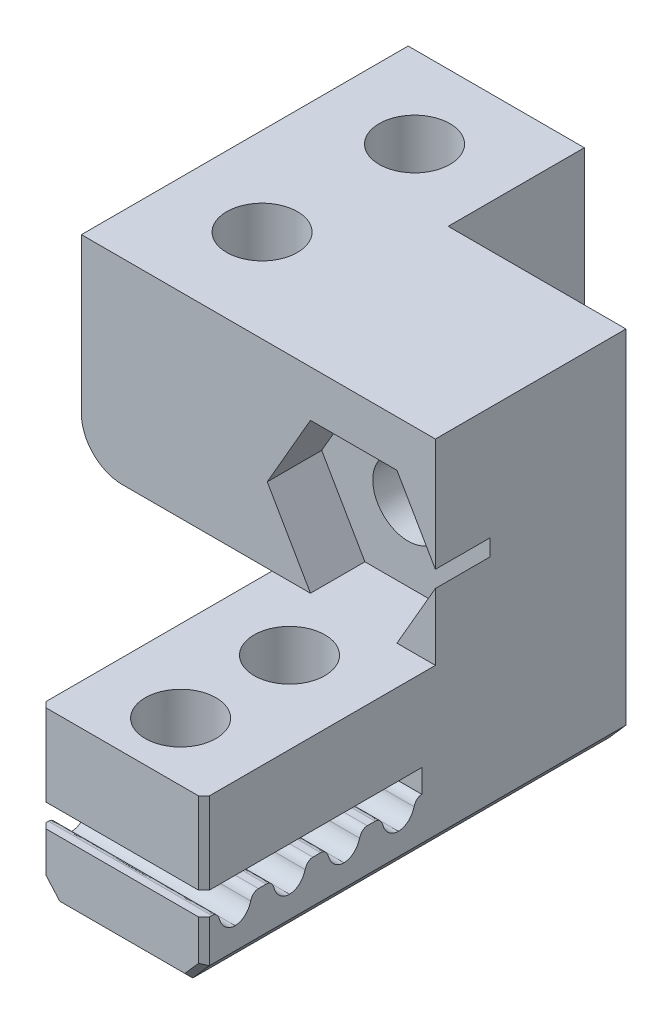
SolidWorks part; units mm, degrees
ref_plane "Front Plane" through (0, 0, 0) normal (0, 0, 1) x (1, 0, 0)
ref_plane "Top Plane" through (0, 0, 0) normal (0, 1, 0) x (1, 0, 0)
ref_plane "Right Plane" through (0, 0, 0) normal (1, 0, 0) x (0, 0, -1)
sketch "Sketch1" plane through (0, 0, 0) normal (0, 0, 1) x (1, 0, 0)
  line L0 (3, 3.05) -> (3, -2.2538)
  line L1 (-3, 3.05) -> (-3, -2.2538)
  line L7 (-3, 3.05) -> (3, 3.05)
  line L13 (-3, -2.2538) -> (-2.3882, -2.95)
  line L14 (3, -2.2538) -> (2.3882, -2.95)
  line L16 (-2.3882, -2.95) -> (2.3882, -2.95)
extrude "Boss-Extrude1" add sketch "Sketch1" along normal blind 13
sketch "Sketch6" plane through (0, 3.05, 0) normal (0, 1, 0) x (1, 0, 0)
  line L0 (-3, -5) -> (-3, 0)
  line L1 (-3, 0) -> (3, 0)
  line L3 (-3, -5) -> (3, -5)
  line L6 (3, -5) -> (3, 0)
  line L7 (3, 0) -> (-3, 0) construction
extrude "Boss-Extrude4" add sketch "Sketch6" along normal blind 5.6
sketch "Sketch16" plane through (0, 3.05, 0) normal (0, 1, 0) x (1, 0, 0)
  line L4 (3, -5) -> (-3, -5)
  line L5 (-3, -5) -> (-3, -13)
  line L6 (-3, -13) -> (3, -13)
  line L7 (3, -13) -> (3, -5)
  line L8 (3, -5) -> (-3, -5)
  line L9 (-3, -5) -> (-3, -13)
  line L10 (-3, -13) -> (3, -13)
  line L11 (3, -13) -> (3, -5)
  dimension "D1" = 0
extrude "Boss-Extrude5" add sketch "Sketch16" along normal blind 0.1
sketch "Sketch18" plane through (0, 0, 0) normal (1, 0, 0) x (0, 0, -1)
  line L0 (-8.8572, -0.0702) -> (-12.8572, -0.0702)
  line L2 (-12.8572, -0.7) -> (-12.7144, -0.7)
  line L3 (-11, -0.7) -> (-10.8572, -0.7)
  line L4 (-10.8572, -0.7) -> (-10.7144, -0.7)
  line L5 (-9, -0.7) -> (-8.8572, -0.7)
  line L6 (-8.8572, -0.7) -> (-8.7144, -0.7)
  line L7 (-7, -0.7) -> (-6.8572, -0.7)
  line L8 (-6.8572, -0.7) -> (-6.7144, -0.7)
  line L9 (-5, -0.0702) -> (-5, -0.7)
  line L11 (-5, -0.0702) -> (-8.8572, -0.0702)
  line L12 (-13, -2.95) -> (0, -2.95) construction
  line L13 (-5.8572, -1.45) -> (-5, -1.45) construction
  line L14 (-5, -1.45) -> (-11.8572, -1.45) construction
  line L15 (-5, 3.15) -> (-5, -1.45) construction
  line L16 (-5, -0.7) -> (-5, -1.45) construction
  line L17 (-12.8572, -0.0702) -> (-13, -0.0702)
  line L20 (-13, -0.0702) -> (-13, -0.7)
  line L22 (-12.8572, -0.7) -> (-13, -0.7)
  spline S0 degree 2 poles (-12.7144, -0.7) (-12.5198, -0.7) (-12.43, -0.9509) knots 0.103448 0.103448 0.103448 0.137931 0.137931 0.137931
  spline S1 degree 3 poles (-12.43, -0.9509) (-12.3594, -1.2388) (-12.13, -1.45) (-11.8572, -1.45) knots 0.137931 0.137931 0.137931 0.137931 0.172414 0.172414 0.172414 0.172414
  spline S2 degree 3 poles (-11.8572, -1.45) (-11.5844, -1.45) (-11.355, -1.2388) (-11.2844, -0.9509) knots 0.172414 0.172414 0.172414 0.172414 0.206897 0.206897 0.206897 0.206897
  spline S3 degree 2 poles (-11.2844, -0.9509) (-11.1946, -0.7) (-11, -0.7) knots 0.206897 0.206897 0.206897 0.241379 0.241379 0.241379
  spline S4 degree 2 poles (-10.7144, -0.7) (-10.5198, -0.7) (-10.43, -0.9509) knots 0.310345 0.310345 0.310345 0.344828 0.344828 0.344828
  spline S5 degree 3 poles (-10.43, -0.9509) (-10.3594, -1.2388) (-10.13, -1.45) (-9.8572, -1.45) knots 0.344828 0.344828 0.344828 0.344828 0.37931 0.37931 0.37931 0.37931
  spline S6 degree 3 poles (-9.8572, -1.45) (-9.5844, -1.45) (-9.355, -1.2388) (-9.2844, -0.9509) knots 0.37931 0.37931 0.37931 0.37931 0.413793 0.413793 0.413793 0.413793
  spline S7 degree 2 poles (-9.2844, -0.9509) (-9.1946, -0.7) (-9, -0.7) knots 0.413793 0.413793 0.413793 0.448276 0.448276 0.448276
  spline S8 degree 2 poles (-8.7144, -0.7) (-8.5198, -0.7) (-8.43, -0.9509) knots 0.517241 0.517241 0.517241 0.551724 0.551724 0.551724
  spline S9 degree 3 poles (-8.43, -0.9509) (-8.3594, -1.2388) (-8.13, -1.45) (-7.8572, -1.45) knots 0.551724 0.551724 0.551724 0.551724 0.586207 0.586207 0.586207 0.586207
  spline S10 degree 3 poles (-7.8572, -1.45) (-7.5844, -1.45) (-7.355, -1.2388) (-7.2844, -0.9509) knots 0.586207 0.586207 0.586207 0.586207 0.62069 0.62069 0.62069 0.62069
  spline S11 degree 2 poles (-7.2844, -0.9509) (-7.1946, -0.7) (-7, -0.7) knots 0.62069 0.62069 0.62069 0.655172 0.655172 0.655172
  spline S12 degree 2 poles (-6.7144, -0.7) (-6.5198, -0.7) (-6.43, -0.9509) knots 0.724138 0.724138 0.724138 0.758621 0.758621 0.758621
  spline S13 degree 3 poles (-6.43, -0.9509) (-6.3594, -1.2388) (-6.13, -1.45) (-5.8572, -1.45) knots 0.758621 0.758621 0.758621 0.758621 0.793103 0.793103 0.793103 0.793103
  spline S14 degree 3 poles (-5.8572, -1.45) (-5.5844, -1.45) (-5.355, -1.2388) (-5.2844, -0.9509) knots 0.793103 0.793103 0.793103 0.793103 0.827586 0.827586 0.827586 0.827586
  spline S15 degree 2 poles (-5.2844, -0.9509) (-5.1946, -0.7) (-5, -0.7) knots 0.827586 0.827586 0.827586 0.862069 0.862069 0.862069
  dimension "D1" = 1.5
  dimension "D2" = 1.3798
extrude "Cut-Extrude6" cut sketch "Sketch18" against normal blind 3.6 and the other way blind 4
sketch "Sketch15" plane through (0, 8.65, 0) normal (0, 1, 0) x (1, 0, 0)
  line L0 (0, -13) -> (0, -5) construction
  line L1 (-3, -13) -> (3, -13) construction
  line L2 (-3, -5) -> (3, -5) construction
  line L3 (2.008, -10.7144) -> (2.008, -11) construction
  line L4 (3, -10.7144) -> (-3, -10.7144) construction
  line L5 (3, -11) -> (-3, -11) construction
  line L6 (2.008, -10.8572) -> (0, -10.8572) construction
  line L7 (1.0382, -6.7144) -> (1.0382, -7) construction
  line L8 (3, -6.7144) -> (-3, -6.7144) construction
  line L9 (3, -7) -> (-3, -7) construction
  line L10 (1.0382, -6.8572) -> (0, -6.8572) construction
  circle A0 centre (0, -6.8572) radius 1.5 construction
  circle A1 centre (0, -10.8572) radius 1.5 construction
  circle A2 centre (0, -10.8572) radius 1.3
  circle A4 centre (0, -6.8572) radius 1.3
  dimension "D1" = 2.6
  dimension "D2" = 2.6
extrude "Cut-Extrude7" cut sketch "Sketch15" against normal up to surface (8.7202 mm away) up to face at (0, -0.0702, 9)
sketch "Sketch19" plane through (0, -0.0702, 0) normal (0, -1, 0) x (1, 0, 0)
  line L4 (-3, 13) -> (-3, 5)
  line L5 (-3, 5) -> (3, 5)
  line L6 (3, 5) -> (3, 13)
  line L7 (3, 13) -> (-3, 13)
  line L8 (-3, 13) -> (-3, 5)
  line L9 (-3, 5) -> (3, 5)
  line L10 (3, 5) -> (3, 13)
  line L11 (3, 13) -> (-3, 13)
  circle A0 centre (0, 10.8572) radius 1.3 construction
  circle A1 centre (0, 6.8572) radius 1.3 construction
  circle A2 centre (0, 10.8572) radius 1.3
  circle A3 centre (0, 6.8572) radius 1.3
  dimension "D1" = 0
extrude "Cut-Extrude8" cut sketch "Sketch19" against normal blind 0.2202
sketch "Sketch12" plane through (0, 0, 5) normal (0, 0, 1) x (1, 0, 0)
  circle A0 centre (0, 5.85) radius 1.5 construction
  circle A1 centre (0, 5.85) radius 1.2
extrude "Cut-Extrude5" cut sketch "Sketch12" against normal blind 6
sketch "Sketch21" plane through (0, 0, 0) normal (0, 0, -1) x (-1, 0, 0)
  line L10 (-2.3882, -2.95) -> (2.3882, -2.95)
  line L11 (2.3882, -2.95) -> (3, -2.2538)
  line L12 (3, -2.2538) -> (3, 8.65)
  line L13 (3, 8.65) -> (-3, 8.65)
  line L14 (-3, 8.65) -> (-3, -2.2538)
  line L15 (-3, -2.2538) -> (-2.3882, -2.95)
  line L19 (-2.3882, -2.95) -> (2.3882, -2.95)
  line L20 (2.3882, -2.95) -> (3, -2.2538)
  line L21 (3, -2.2538) -> (3, 8.65)
  line L22 (3, 8.65) -> (-3, 8.65)
  line L23 (-3, 8.65) -> (-3, -2.2538)
  line L24 (-3, -2.2538) -> (-2.3882, -2.95)
  circle A0 centre (0, 5.85) radius 1.2 construction
  circle A1 centre (0, 5.85) radius 1.2
  dimension "D1" = 0
extrude "Boss-Extrude6" add sketch "Sketch21" along normal blind 2.5
sketch "Sketch24" plane through (0, 0, 5) normal (0, 0, 1) x (1, 0, 0)
  line L4 (-3, 8.65) -> (-3, 3.15)
  line L5 (-3, 3.15) -> (3, 3.15)
  line L6 (3, 3.15) -> (3, 8.65)
  line L7 (3, 8.65) -> (-3, 8.65)
  line L8 (-3, 8.65) -> (-3, 3.15)
  line L9 (-3, 3.15) -> (3, 3.15)
  line L10 (3, 3.15) -> (3, 8.65)
  line L11 (3, 8.65) -> (-3, 8.65)
  dimension "D1" = 0
extrude "Cut-Extrude10" cut sketch "Sketch24" against normal blind 8.5
sketch "Sketch25" plane through (0, 3.15, 0) normal (0, 1, 0) x (1, 0, 0)
  line L2 (0, -4.5) -> (3.5, -4.5)
  line L3 (3.5, 2.5) -> (-10, 2.5)
  line L5 (0, -4.5) -> (-10, -4.5)
  line L6 (-10, 2.5) -> (-10, -4.5)
  line L8 (3.5, 2.5) -> (3.5, -4.5)
  dimension "D1" = 7
extrude "Boss-Extrude8" add sketch "Sketch25" along normal blind 7.2
fillet "Fillet4" radius 1.5 1 edges at (-10, 3.15, 1)
sketch "Sketch26" plane through (0, 0, 4.5) normal (0, 0, 1) x (1, 0, 0)
  circle A0 centre (0, 5.9) radius 1.5 construction
  circle A1 centre (0, 5.9) radius 1.5 construction
  circle A2 centre (0, 5.9) radius 1.3
  dimension "D1" = 2.6
extrude "Cut-Extrude11" cut sketch "Sketch26" against normal blind 10
chamfer "Chamfer1" distance 0.2 angle 45 5 edges at (-3, -1.4769, 13) (-2.6941, -2.6019, 13) (0, -2.95, 13) (2.6941, -2.6019, 13) (3, -1.4769, 13)
sketch "Sketch29" plane through (0, 0, -2.5) normal (0, 0, -1) x (-1, 0, 0)
  line L2 (3.53, 3.15) -> (3.53, 10.35)
  line L13 (3, 3.15) -> (8.5, 3.15)
  line L14 (10, 4.65) -> (10, 10.35)
  line L15 (10, 10.35) -> (-3.5, 10.35)
  line L16 (-3.5, 10.35) -> (-3.5, 3.15)
  line L17 (-3.5, 3.15) -> (-3, 3.15)
  line L18 (-3, 3.15) -> (-3, -2.2538)
  line L19 (-3, -2.2538) -> (-2.3882, -2.95)
  line L20 (-2.3882, -2.95) -> (2.3882, -2.95)
  line L24 (2.3882, -2.95) -> (3, -2.2538)
  line L25 (3, -2.2538) -> (3, 3.15)
  line L26 (3.53, 3.15) -> (8.5, 3.15)
  line L27 (10, 4.65) -> (10, 10.35)
  line L28 (10, 10.35) -> (3.53, 10.35)
  arc A2 (8.5, 3.15) -> (10, 4.65) centre (8.5, 4.65) ccw
  arc A4 (8.5, 3.15) -> (10, 4.65) centre (8.5, 4.65) ccw
  dimension "D1" = 0
extrude "Boss-Extrude9" add sketch "Sketch29" along normal blind 5
sketch "Sketch31" plane through (0, 10.35, 0) normal (0, 1, 0) x (1, 0, 0)
  line L0 (-6.765, 7.5) -> (-6.765, 1.5) construction
  line L1 (-10, 7.5) -> (-3.53, 7.5) construction
  line L3 (-0.015, 2.5) -> (0, -4.5) construction
  line L5 (-6.765, 1.5) -> (-4.5254, 1.5) construction
  line L7 (-3.53, -1.1) -> (-10, -1.1) construction
  line L8 (-10, 7.5) -> (-10, -4.5) construction
  line L9 (3.5, 2.5) -> (-3.53, 2.5) construction
  line L10 (-3, -4.5) -> (3, -4.5) construction
  line L11 (-10, -4.5) -> (3.5, -4.5) construction
  circle A0 centre (-6.765, 4.5) radius 1.3
  circle A1 centre (-6.765, -1.1) radius 1.3
  circle A2 centre (-6.765, -1.1) radius 2.75 construction
  circle A3 centre (-6.765, 4.5) radius 2.75 construction
  dimension "D1" = 2.6
  dimension "D2" = 3.4
  dimension "D3" = 3
extrude "Cut-Extrude12" cut sketch "Sketch31" against normal blind 8
sketch "Croquis1" plane through (3.5, 0, 0) normal (1, 0, 0) x (0, 0, -1)
  line L1 (9.3685, 16.2518) -> (-11.5995, 16.2518)
  line L2 (9.3685, 16.2518) -> (9.3685, -2.8405)
  line L3 (9.3685, -2.8405) -> (-11.5995, -2.8405)
  line L4 (-11.5995, 16.2518) -> (-11.5995, -2.8405)
extrude "Cortar-Extruir1" cut sketch "Croquis1" against normal up to surface (0.5 mm away) up to face at (3, -0.5166, 8.4383)
sketch "Croquis2" plane through (0, 0, 4.5) normal (0, 0, 1) x (1, 0, 0)
  line L1 (1.5877, 8.65) -> (-1.5877, 8.65)
  line L2 (-1.5877, 8.65) -> (-3.1754, 5.9)
  line L3 (-3.1754, 5.9) -> (-1.5877, 3.15)
  line L4 (-1.5877, 3.15) -> (1.5877, 3.15)
  line L5 (1.5877, 3.15) -> (3.1754, 5.9)
  line L6 (3.1754, 5.9) -> (1.5877, 8.65)
  circle A0 centre (0, 5.9) radius 2.75 construction
  point P1 (3.1754, 5.9)
  dimension "D1" = 5.5
extrude "Cortar-Extruir2" cut sketch "Croquis2" against normal blind 2
